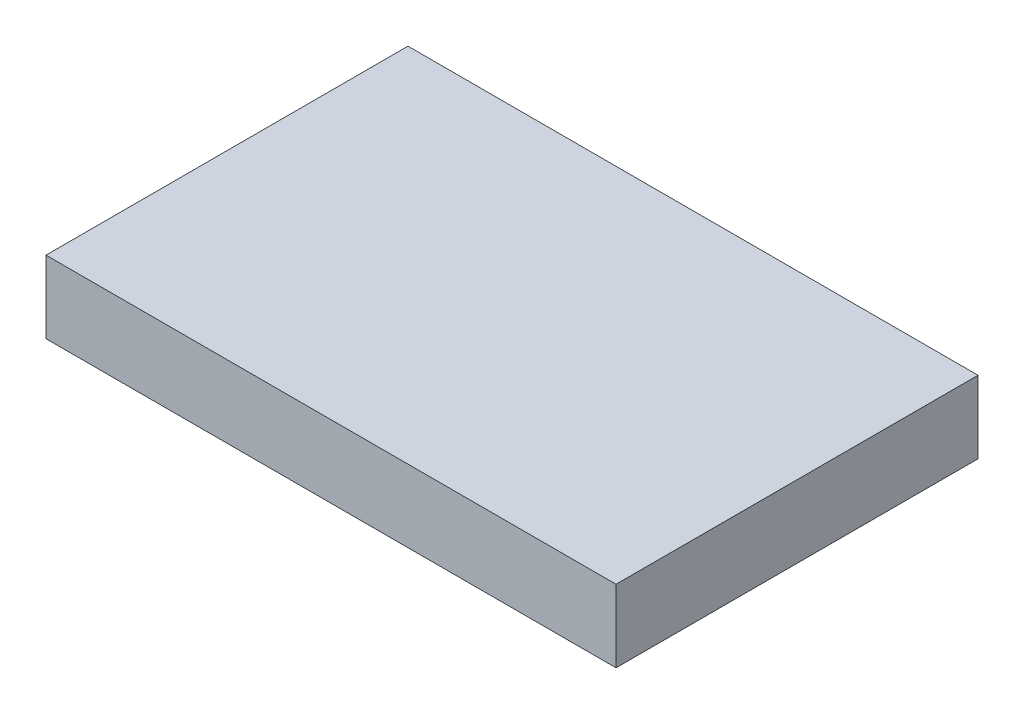
SolidWorks part; units mm, degrees
ref_plane "Front Plane" through (0, 0, 0) normal (0, 0, 1) x (1, 0, 0)
ref_plane "Top Plane" through (0, 0, 0) normal (0, 1, 0) x (1, 0, 0)
ref_plane "Right Plane" through (0, 0, 0) normal (1, 0, 0) x (0, 0, -1)
sketch "Sketch1" plane through (0, 0, 0) normal (0, 1, 0) x (1, 0, 0)
  line L1 (0, 0) -> (200, 0)
  line L2 (0, 0) -> (0, 127)
  line L3 (0, 127) -> (200, 127)
  line L4 (200, 0) -> (200, 127)
  dimension "D1" = 200
  dimension "D2" = 127
extrude "Boss-Extrude1" add sketch "Sketch1" along normal blind 25.4
